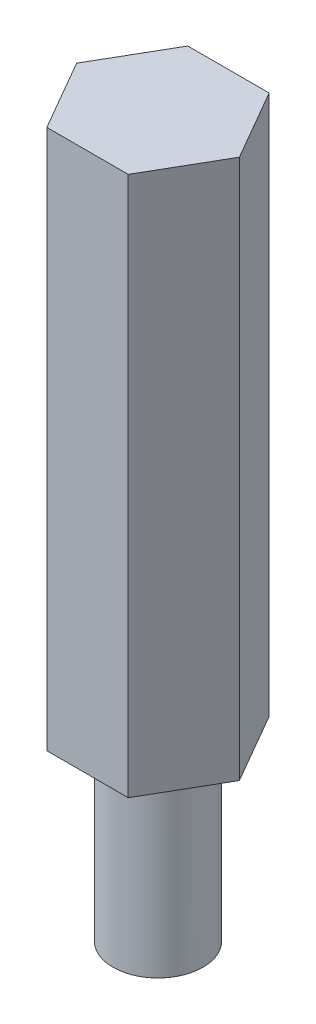
SolidWorks part; units mm, degrees
ref_plane "前视基准面" through (0, 0, 0) normal (0, 0, 1) x (1, 0, 0)
ref_plane "上视基准面" through (0, 0, 0) normal (0, 1, 0) x (1, 0, 0)
ref_plane "右视基准面" through (0, 0, 0) normal (1, 0, 0) x (0, 0, -1)
sketch "草图1" plane through (0, 0, 0) normal (0, 1, 0) x (1, 0, 0)
  line L1 (-1.3568, 2.35) -> (-2.7135, 0)
  line L2 (-2.7135, 0) -> (-1.3568, -2.35)
  line L3 (-1.3568, -2.35) -> (1.3568, -2.35)
  line L4 (1.3568, -2.35) -> (2.7135, 0)
  line L5 (2.7135, 0) -> (1.3568, 2.35)
  line L6 (1.3568, 2.35) -> (-1.3568, 2.35)
  circle A0 centre (0, 0) radius 2.35 construction
  dimension "D1" = 4.7
extrude "凸台-拉伸1" add sketch "草图1" along normal blind 18
sketch "草图2" plane through (0, 0, 0) normal (0, -1, 0) x (1, 0, 0)
  circle A0 centre (0, 0) radius 1.5
  dimension "D1" = 3
extrude "凸台-拉伸2" add sketch "草图2" along normal blind 6
